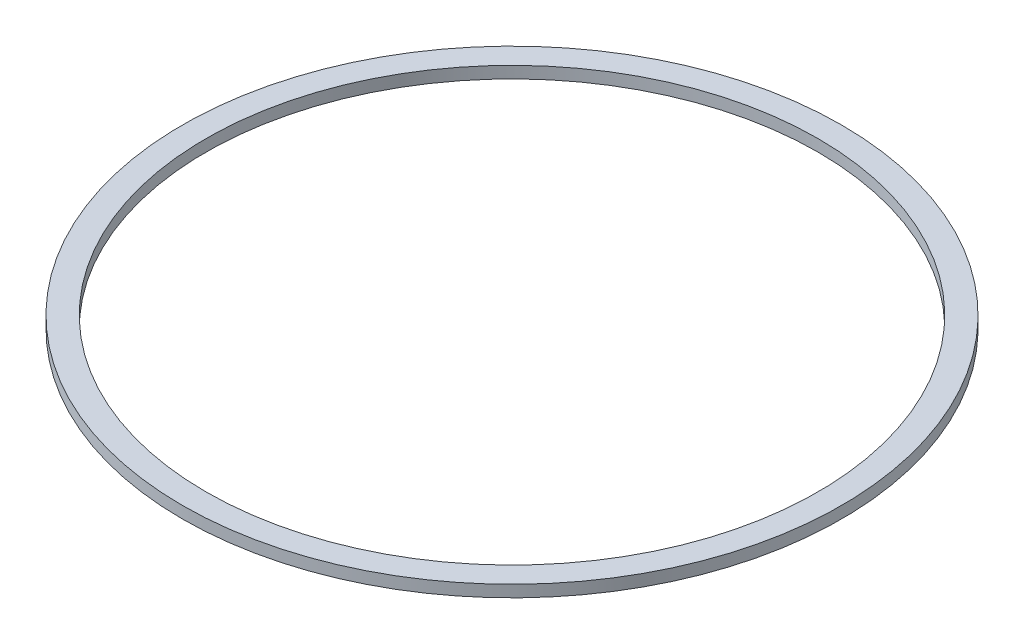
SolidWorks part; units mm, degrees
other "Bearing Outer Race Shim"
ref_plane "Front Plane" through (0, 0, 0) normal (0, 0, 1) x (1, 0, 0)
ref_plane "Top Plane" through (0, 0, 0) normal (0, 1, 0) x (1, 0, 0)
ref_plane "Right Plane" through (0, 0, 0) normal (1, 0, 0) x (0, 0, -1)
sketch3d "Shim blank sketch datum points"
  point P0 (-19.0092, -237.5, -53.2449)
  point P1 (-9.0092, -237.5, -53.2449)
  point P2 (-19.0092, -237.5, -63.2449)
ref_plane "Shim blank sketch plane" through (0, -237.5, 0) normal (0, 1, 0) x (1, 0, 0)
sketch "Shim blank sketch" plane through (0, -237.5, 0) normal (0, 1, 0) x (1, 0, 0)
  circle A0 centre (-19.0092, 53.2449) radius 14
extrude "Shim blank" add sketch "Shim blank sketch" along normal blind 0.5 separate body
sketch3d "Shim bore sketch datum points"
  point P0 (-19.0092, -237.6, -53.2449)
  point P1 (-9.0092, -237.6, -53.2449)
  point P2 (-19.0092, -237.6, -63.2449)
ref_plane "Shim bore sketch plane" through (0, -237.6, 0) normal (0, 1, 0) x (1, 0, 0)
sketch "Shim bore sketch" plane through (0, -237.6, 0) normal (0, 1, 0) x (1, 0, 0)
  circle A0 centre (-19.0092, 53.2449) radius 13
extrude "Shim bore" cut sketch "Shim bore sketch" along normal blind 0.7
